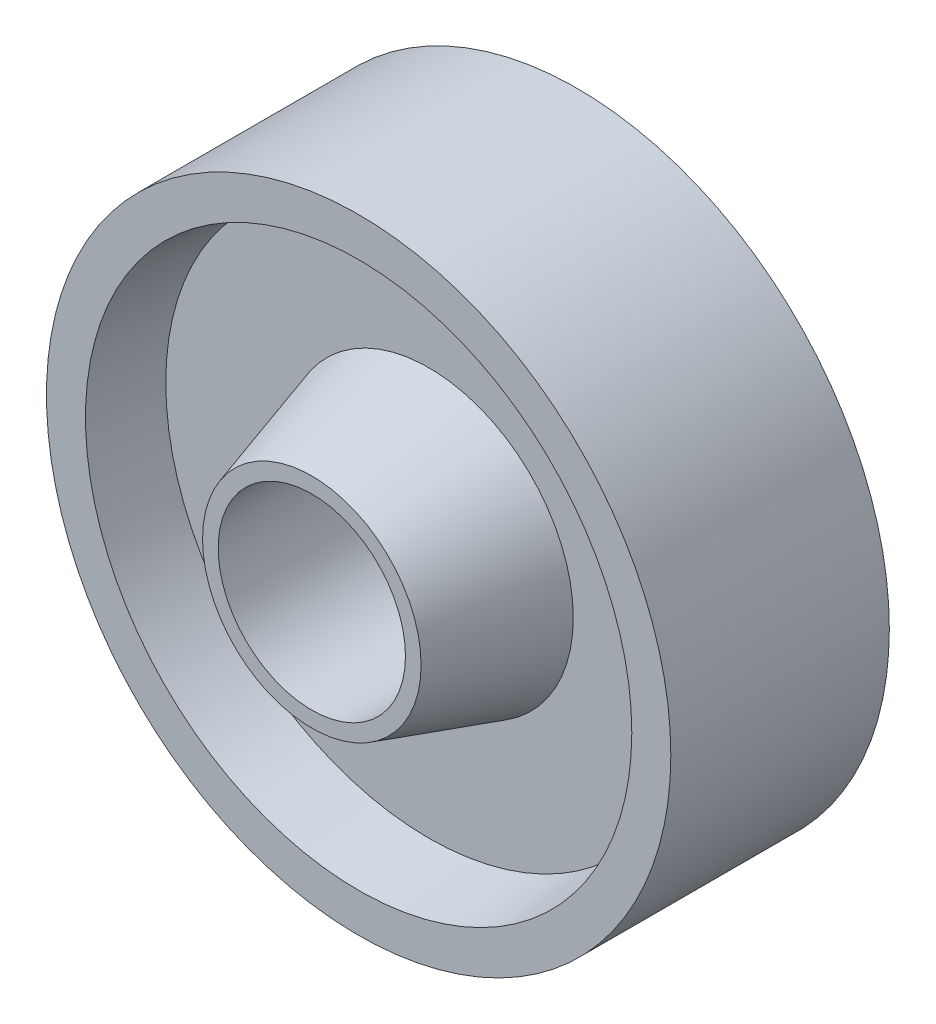
SolidWorks part; units mm, degrees
ref_plane "Front Plane" through (0, 0, 0) normal (0, 0, 1) x (1, 0, 0)
ref_plane "Top Plane" through (0, 0, 0) normal (0, 1, 0) x (1, 0, 0)
ref_plane "Right Plane" through (0, 0, 0) normal (1, 0, 0) x (0, 0, -1)
sketch "Sketch1" plane through (0, 0, 0) normal (1, 0, 0) x (0, 0, -1)
  line L1 (-20, 12) -> (20, 12)
  line L2 (20, 12) -> (20, 14)
  line L4 (5, 18.5) -> (20, 14)
  line L6 (-14, 40) -> (14, 40)
  line L7 (14, 40) -> (14, 35)
  line L9 (14, 35) -> (5, 33.7143)
  line L10 (-5, 12) -> (5, 12)
  line L11 (5, 18.5) -> (5, 33.7143)
  line L12 (0, 0) -> (15.6487, 0)
  line L13 (-20, 12) -> (-20, 14)
  line L14 (-5, 18.5) -> (-5, 33.7143)
  line L15 (-14, 35) -> (-5, 33.7143)
  line L16 (-14, 40) -> (-14, 35)
  line L17 (-5, 18.5) -> (-20, 14)
  dimension "D1" = 5
  dimension "D2" = 14
  dimension "D3" = 15.6487
  dimension "D4" = 20
  dimension "D5" = 5
  dimension "D6" = 12
  dimension "D7" = 14
  dimension "D8" = 18.5
  dimension "D9" = 33.7143
  dimension "D10" = 35
  dimension "D11" = 40
revolve "Revolve1" add sketch "Sketch1" angle 360 about L12
